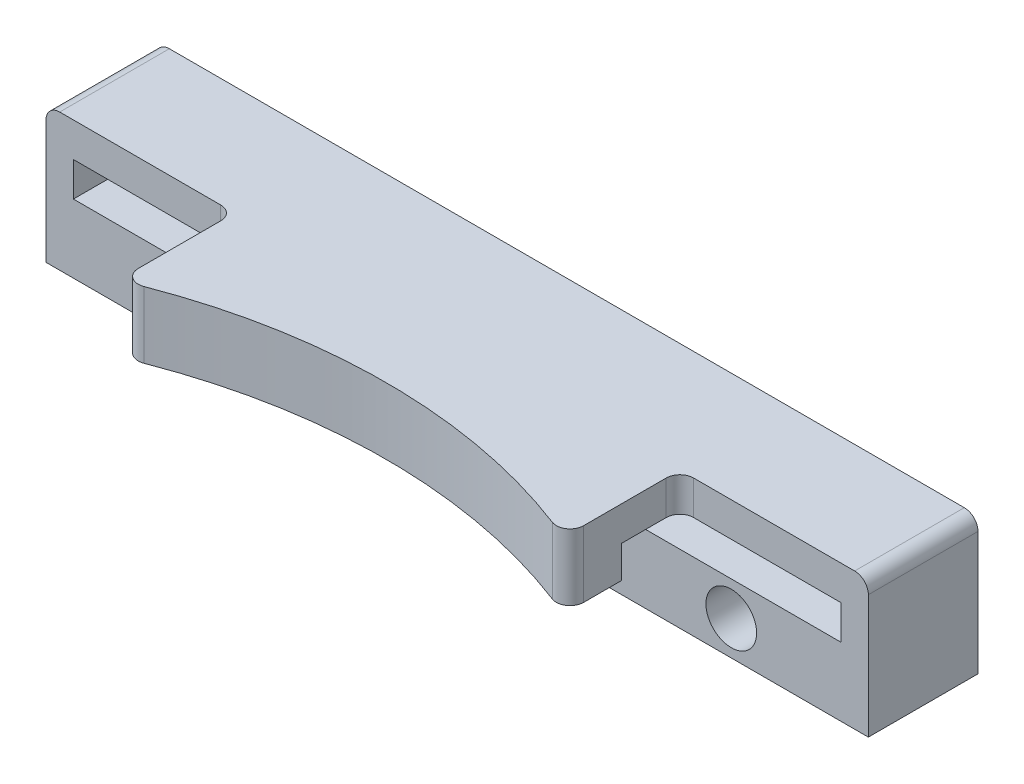
SolidWorks part; units mm, degrees
ref_plane "Front" through (0, 0, 0) normal (0, 0, 1) x (1, 0, 0)
ref_plane "Top" through (0, 0, 0) normal (0, 1, 0) x (1, 0, 0)
ref_plane "Right" through (0, 0, 0) normal (1, 0, 0) x (0, 0, -1)
sketch "Sketch1" plane through (0, 0, 0) normal (0, 0, 1) x (1, 0, 0)
  line L0 (-40, 5) -> (40, 5) construction
  line L1 (-60, 20) -> (60, 20)
  line L2 (-60, 20) -> (-60, 0)
  line L3 (-60, 0) -> (60, 0)
  line L4 (60, 20) -> (60, 0)
  line L5 (-56, 10) -> (56, 10)
  line L6 (-56, 10) -> (-56, 15)
  line L7 (-56, 15) -> (56, 15)
  line L8 (56, 10) -> (56, 15)
  circle A0 centre (-40, 5) radius 2
  circle A1 centre (40, 5) radius 2
  point P8 (0, 0)
  point P10 (0, 10)
  point P15 (0, 5)
  dimension "D6" = 80
  dimension "D7" = 4
  dimension "D1" = 120
  dimension "D2" = 20
  dimension "D3" = 5
  dimension "D4" = 10
  dimension "D5" = 5
  dimension "D8" = 112
extrude "Boss-Extrude1" add sketch "Sketch1" along normal blind 16
sketch "Sketch2" plane through (0, 0, 16) normal (0, 0, 1) x (1, 0, 0)
  circle A0 centre (-40, 5) radius 3.7
  circle A1 centre (40, 5) radius 3.7
  dimension "D1" = 7.4
extrude "Cut-Extrude1" cut sketch "Sketch2" against normal blind 8
sketch "Sketch3" plane through (0, 20, 0) normal (0, 1, 0) x (1, 0, 0)
  line L0 (-32.5, -33) -> (-32.5, -16)
  line L1 (60, -16) -> (-60, -16) construction
  line L2 (-32.5, -16) -> (32.5, -16)
  line L3 (32.5, -16) -> (32.5, -33)
  line L4 (60, 0) -> (-60, 0) construction
  arc A0 (-32.5, -33) -> (32.5, -33) centre (0, -109.3724) cw
  point P7 (0, -16)
  point P8 (0, -16)
  point P11 (0, 0)
  point P12 (27.8928, -75)
  dimension "D3" = 83
  dimension "D1" = 33
  dimension "D2" = 65
extrude "Boss-Extrude2" add sketch "Sketch3" against normal up to surface (5 mm away) up to face at (0, 15, 8)
sketch "Sketch4" plane through (0, 15, 0) normal (0, -1, 0) x (1, 0, 0)
  line L0 (-32.5, 16) -> (-32.5, 33) construction
  line L1 (32.5, 33) -> (32.5, 16) construction
  line L2 (-32.5, 24.52) -> (-32.5, 33)
  line L3 (32.5, 24.52) -> (32.5, 33)
  arc A0 (-32.5, 33) -> (32.5, 33) centre (0, 109.3724) ccw
  arc A1 (-32.5, 24.52) -> (32.5, 24.52) centre (0, 100.8924) ccw
  arc A2 (-32.5, 33) -> (32.5, 33) centre (0, 109.3724) ccw construction
  dimension "D1" = 8.48
extrude "Boss-Extrude3" add sketch "Sketch4" along normal blind 4.7
fillet "Fillet1" radius 2 6 edges at (-60, 20, 8) (60, 20, 8) (32.5, 17.5, 16) (-32.5, 17.5, 16) (-32.5, 15.15, 33) (32.5, 15.15, 33)
sketch "Sketch5" plane through (0, 0, 16) normal (0, 0, 1) x (1, 0, 0)
  circle A0 centre (-56, 15) radius 0.5
  circle A1 centre (-56, 10) radius 0.5
  circle A2 centre (56, 15) radius 0.5
  circle A3 centre (56, 10) radius 0.5
  dimension "D1" = 1
extrude "Cut-Extrude2" [suppressed] cut sketch "Sketch5" against normal through all
fillet "Fillet2" [suppressed] radius 0.5
